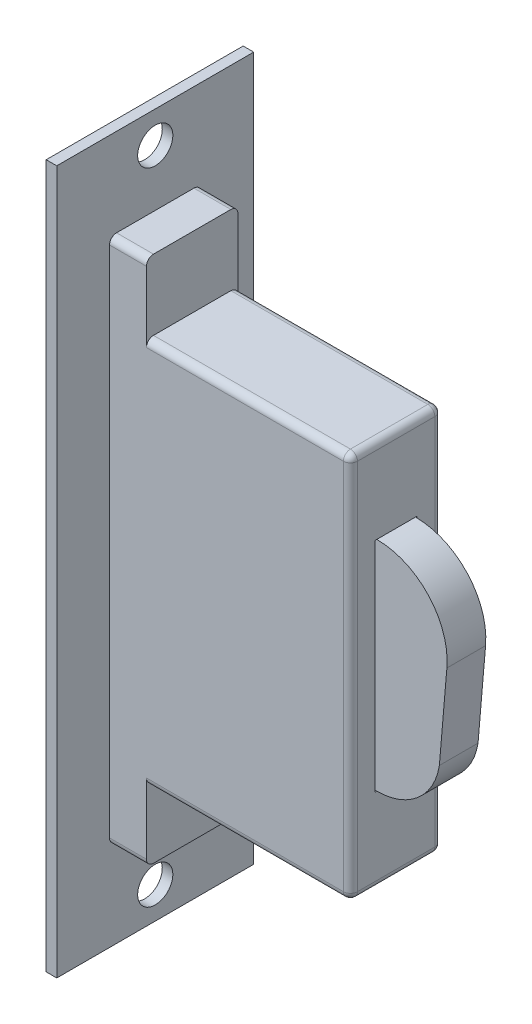
SolidWorks part; units mm, degrees
ref_plane "前视基准面" through (0, 0, 0) normal (0, 0, 1) x (1, 0, 0)
ref_plane "上视基准面" through (0, 0, 0) normal (0, 1, 0) x (1, 0, 0)
ref_plane "右视基准面" through (0, 0, 0) normal (1, 0, 0) x (0, 0, -1)
other "Configuration Table"
sketch "草图1" plane through (0, 0, 0) normal (0, 0, 1) x (1, 0, 0)
  line L0 (-62.1853, 0) -> (62.6908, 0) construction
  line L1 (0, -1.0111) -> (0, 37.5)
  line L2 (6, 37.5) -> (0, 37.5)
  line L3 (6, 37.5) -> (6, 27.4969)
  line L4 (35, 27.5) -> (35, 27.4969)
  line L5 (35, -27.5) -> (35, 27.5)
  line L6 (6, 27.4969) -> (35, 27.4969)
  line L7 (6, -27.4969) -> (35, -27.4969)
  line L8 (6, -37.5) -> (6, -27.4969)
  line L9 (6, -37.5) -> (0, -37.5)
  line L10 (0, 1.0111) -> (0, -37.5)
  point P11 (35, 0)
  dimension "D1" = 6
  dimension "D2" = 29
  dimension "D3" = 75
  dimension "D4" = 55
extrude "凸台-拉伸1" add sketch "草图1" along normal mid plane 13 contours L10 L0 L5 L6 L3 L2 L1 | L0 L1 L10 L9 L8 L7 L5
sketch "草图2" plane through (0, 0, 0) normal (-1, 0, 0) x (0, 0, 1)
  line L0 (-23.8291, 0) -> (22.0306, 0) construction
  line L1 (0, 51.8451) -> (0, -56.8454) construction
  line L3 (-14, 50) -> (14, 50)
  line L4 (-14, 50) -> (-14, -50)
  line L5 (-14, -50) -> (14, -50)
  line L6 (14, 50) -> (14, -50)
  line L7 (-14, 50) -> (14, -50) construction
  line L8 (-14, -50) -> (14, 50) construction
  circle A0 centre (0, -45.5) radius 2.5
  circle A1 centre (0, 45.5) radius 2.5
  point P5 (0, 0)
  point P16 (0, -50)
  dimension "D3" = 5
  dimension "D4" = 4.5
  dimension "D1" = 28
  dimension "D2" = 100
extrude "凸台-拉伸2" add sketch "草图2" along normal mid plane 1.5
sketch "草图3" plane through (35, 0, 0) normal (1, 0, 0) x (0, 0, -1)
  line L1 (-3, -15.5) -> (3, -15.5)
  line L2 (-3, -15.5) -> (-3, 15.5)
  line L3 (-3, 15.5) -> (3, 15.5)
  line L4 (3, -15.5) -> (3, 15.5)
  line L5 (-3, -15.5) -> (3, 15.5) construction
  line L6 (-3, 15.5) -> (3, -15.5) construction
  point P0 (0, 0)
  dimension "D1" = 6
  dimension "D2" = 31
extrude "切除-拉伸1" cut sketch "草图3" against normal blind 5
sketch "草图4" plane through (0, -27.4969, 0) normal (0, -1, 0) x (1, 0, 0)
  line L0 (-7.2558, 0) -> (44.8447, 0) construction
  line L1 (35, 6.5) -> (35, -6.5) construction
  line L2 (28.5, 2.75) -> (15, 2.75)
  line L3 (28.5, 2.75) -> (28.5, -2.75)
  line L4 (28.5, -2.75) -> (15, -2.75)
  line L5 (15, 2.75) -> (15, -2.75)
  line L6 (28.5, 2.75) -> (15, -2.75) construction
  line L7 (28.5, -2.75) -> (15, 2.75) construction
  point P3 (21.75, 0)
  dimension "D1" = 5.5
  dimension "D2" = 13.5
  dimension "D3" = 20
extrude "切除-拉伸2" cut sketch "草图4" against normal blind 5
sketch "草图5" plane through (0, 0, 0) normal (0, 0, 1) x (1, 0, 0)
  line L0 (30, -15.5) -> (30, 15.5) construction
  line L1 (30, -15.5) -> (30, 15.5)
  line L2 (-24.1798, 0) -> (49.3233, 0) construction
  line L3 (35, -15.5) -> (35, 15.5) construction
  line L4 (35, -15.5) -> (35, 15.5) construction
  line L5 (43.8929, -7.8846) -> (44.9637, 4.6487)
  line L6 (35, 15.5) -> (30, 15.5)
  line L7 (30, -15.5) -> (35, -15.5)
  arc A0 (44.9637, 4.6487) -> (35, 15.5) centre (35, 5.5) ccw
  arc A2 (35, -15.5) -> (43.8929, -7.8846) centre (35, -6.5) ccw
  dimension "D1" = 10
  dimension "D2" = 9
extrude "凸台-拉伸3" add sketch "草图5" along normal mid plane 5.5
fillet "圆角1" radius 1 4 edges at (3.375, -37.5, -6.5) (3.375, -37.5, 6.5) (3.375, 37.5, 6.5) (3.375, 37.5, -6.5)
fillet "圆角2" radius 1 8 edges at (20.5, -27.4969, -6.5) (20.5, -27.4969, 6.5) (35, -27.4969, 0) (35, 0, 6.5) (35, 0, -6.5) (35, 27.4969, 0) (20.5, 27.4969, 6.5) (20.5, 27.4969, -6.5)
